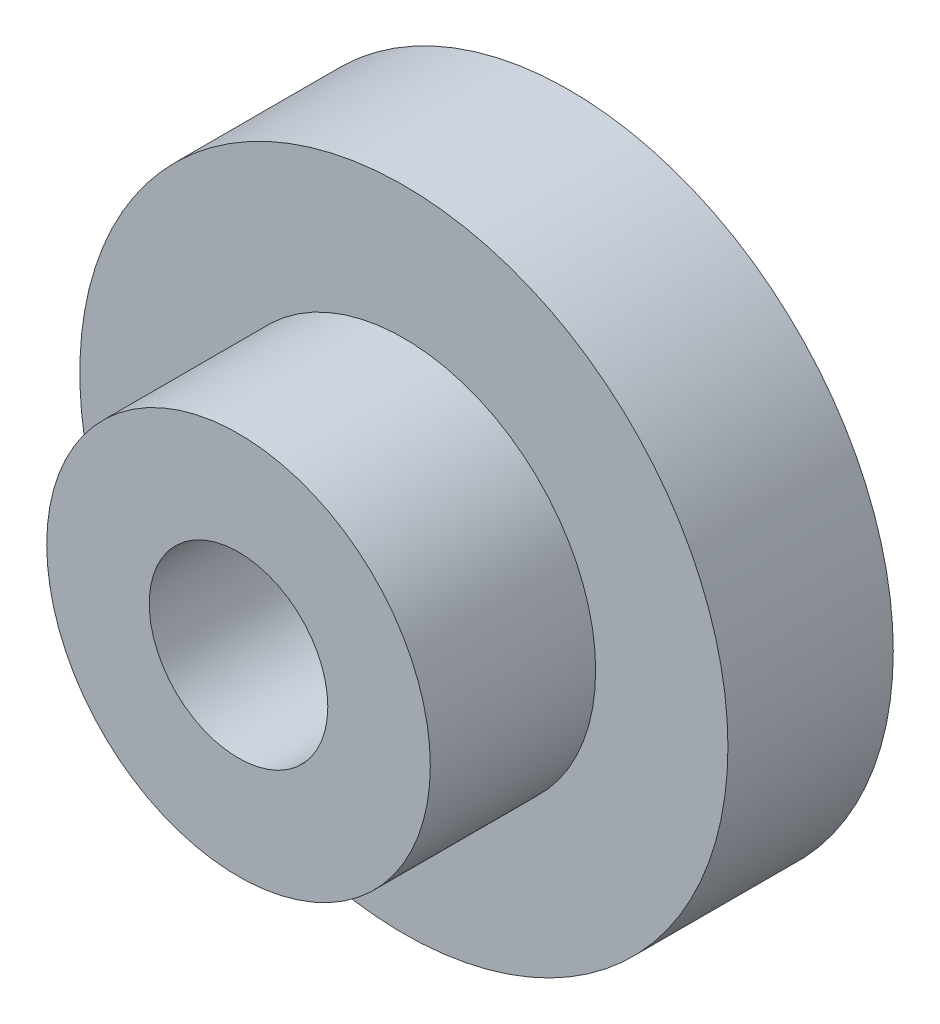
SolidWorks part; units mm, degrees
material "POM 乙缩醛共聚物"
ref_plane "前视基准面" through (0, 0, 0) normal (0, 0, 1) x (1, 0, 0)
ref_plane "上视基准面" through (0, 0, 0) normal (0, 1, 0) x (1, 0, 0)
ref_plane "右视基准面" through (0, 0, 0) normal (1, 0, 0) x (0, 0, -1)
sketch "草图1" plane through (0, 0, 0) normal (0, 1, 0) x (1, 0, 0)
  line L0 (0, 0) -> (0, 5.677) construction
  line L1 (-1.35, 5) -> (-4.9, 5)
  line L2 (-4.9, 5) -> (-4.9, 2.5)
  line L3 (-4.9, 2.5) -> (-2.9, 2.5)
  line L4 (-2.9, 2.5) -> (-2.9, 0)
  line L5 (-2.9, 0) -> (-1.35, 0)
  line L6 (-1.35, 5) -> (-1.35, 0)
  dimension "D1" = 5
  dimension "D2" = 2.7
  dimension "D3" = 5.8
  dimension "D4" = 9.8
  dimension "D5" = 2.5
revolve "旋转1" add sketch "草图1" angle 360 about L0
